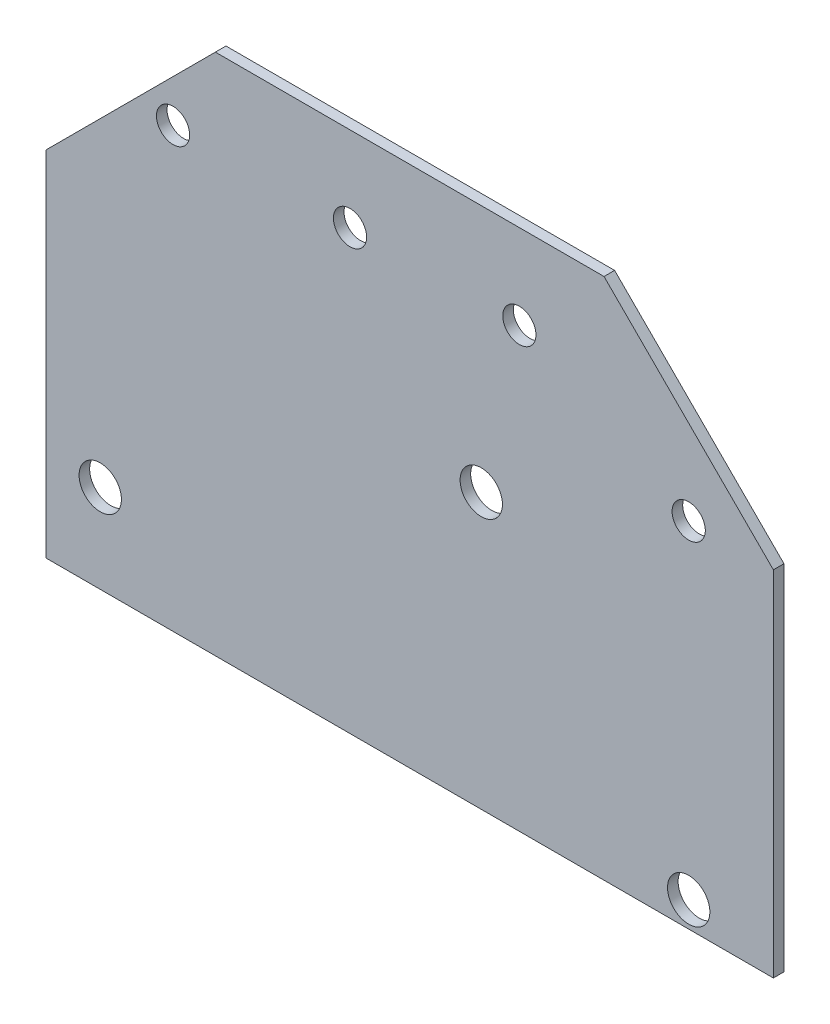
SolidWorks part; units mm, degrees
ref_plane "Front Plane" through (0, 0, 0) normal (0, 0, 1) x (1, 0, 0)
ref_plane "Top Plane" through (0, 0, 0) normal (0, 1, 0) x (1, 0, 0)
ref_plane "Right Plane" through (0, 0, 0) normal (1, 0, 0) x (0, 0, -1)
sketch "Sketch1" plane through (0, 0, 0) normal (0, 0, 1) x (1, 0, 0)
  line L0 (233.807, -12.7) -> (233.807, -65.7225)
  line L1 (317.5, 12.7) -> (-317.5, 12.7) construction
  line L3 (342.9, -65.7225) -> (342.9, -12.7)
  line L4 (317.5, 12.7) -> (259.207, 12.7)
  line L5 (342.9, -214.3125) -> (342.9, 446.0875) construction
  line L6 (262.8977, -93.6625) -> (262.8977, -65.7225) construction
  line L8 (342.9, -12.7) -> (317.5, 12.7)
  line L9 (233.807, -65.7225) -> (342.9, -65.7225)
  line L10 (259.207, 12.7) -> (233.807, -12.7)
  line L11 (260.35, -93.6625) -> (330.2, -93.6625) construction
  circle A0 centre (227.457, 0) radius 6.35 construction
  point P0 (233.807, 12.7)
  point P6 (342.9, 12.7)
  point P13 (0, 0)
  dimension "D1" = 27.94
extrude "Boss-Extrude1" add sketch "Sketch1" along normal blind 1.5875
hole_wizard "#10 Clearance Hole1" positions "Sketch2" profile "Sketch3" hole size "#10" standard "ANSI Inch" end condition through all
sketch "Sketch2" plane through (0, 0, 0) normal (0, 0, -1) x (-1, 0, 0)
  point P0 (-330.2, -12.7)
  point P3 (-304.8, 0)
  point P6 (-279.4, 0)
  point P9 (-252.857, 0)
sketch "Sketch3" plane through (330.2, -12.7, 0) normal (1, 0, 0) x (0, 1, 0)
  line L0 (0, 0) -> (0, 1.5875)
  line L1 (0, 1.5875) -> (2.4892, 1.5875)
  line L2 (2.4892, 1.5875) -> (2.4892, 0)
  line L5 (2.4892, 0) -> (0, 0)
  line L11 (0, -6.35) -> (0, 107.95) construction
  dimension "Thru Hole Dia." = 4.9784
  dimension "Thru Hole Depth" = 1.5875
hole_wizard "1/4 (0.25) Diameter Hole1" positions "Sketch4" profile "Sketch5" hole size "1/4" standard "ANSI Inch" end condition through all
sketch "Sketch4" plane through (0, 0, 0) normal (0, 0, -1) x (-1, 0, 0)
  point P0 (-330.2, -61.9125)
sketch "Sketch5" plane through (330.2, -61.9125, 0) normal (1, 0, 0) x (0, 1, 0)
  line L0 (0, 0) -> (0, 1.5875)
  line L1 (0, 1.5875) -> (3.175, 1.5875)
  line L2 (3.175, 1.5875) -> (3.175, 0)
  line L5 (3.175, 0) -> (0, 0)
  line L11 (0, -6.35) -> (0, 107.95) construction
  dimension "Thru Hole Dia." = 6.35
  dimension "Thru Hole Depth" = 1.5875
hole_wizard "1/4 (0.25) Diameter Hole2" positions "Sketch6" profile "Sketch7" hole size "1/4" standard "ANSI Inch" end condition through all
sketch "Sketch6" plane through (0, 0, 1.5875) normal (0, 0, 1) x (1, 0, 0)
  point P0 (299.085, -24.5252)
  point P3 (241.935, -52.4652)
sketch "Sketch7" plane through (299.085, -24.5252, 1.5875) normal (1, 0, 0) x (0, -1, 0)
  line L0 (0, 0) -> (0, 1.5875)
  line L1 (0, 1.5875) -> (3.175, 1.5875)
  line L2 (3.175, 1.5875) -> (3.175, 0)
  line L5 (3.175, 0) -> (0, 0)
  line L11 (0, -6.35) -> (0, 107.95) construction
  dimension "Thru Hole Dia." = 6.35
  dimension "Thru Hole Depth" = 1.5875
